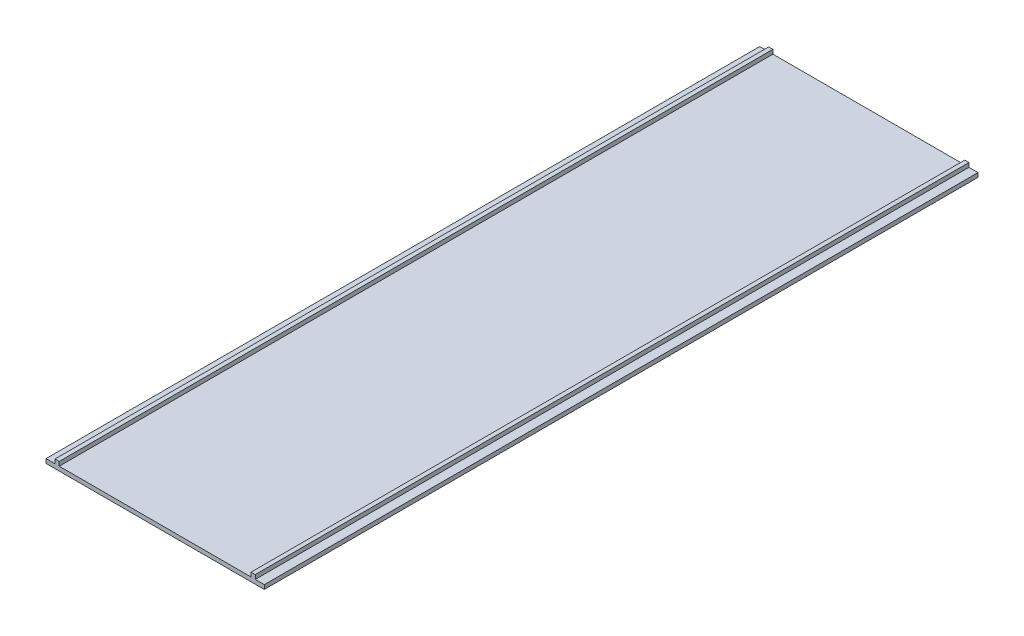
SolidWorks part; units mm, degrees
ref_plane "Спереди" through (0, 0, 0) normal (0, 0, 1) x (1, 0, 0)
ref_plane "Сверху" through (0, 0, 0) normal (0, 1, 0) x (1, 0, 0)
ref_plane "Справа" through (0, 0, 0) normal (1, 0, 0) x (0, 0, -1)
sketch "Эскиз1" plane through (0, 0, 0) normal (0, 1, 0) x (1, 0, 0)
  line L1 (-52, -170) -> (52, -170)
  line L2 (-52, -170) -> (-52, 170)
  line L3 (-52, 170) -> (52, 170)
  line L4 (52, -170) -> (52, 170)
  line L5 (-52, -170) -> (52, 170) construction
  line L6 (-52, 170) -> (52, -170) construction
  point P0 (0, 0)
  dimension "D1" = 104
  dimension "D2" = 340
extrude "Бобышка-Вытянуть1" add sketch "Эскиз1" along normal blind 2
sketch "Эскиз2" plane through (0, 0, 170) normal (0, 0, 1) x (1, 0, 0)
  line L5 (-47.7, 2) -> (-47.7, 4)
  line L6 (-52, 2) -> (52, 2) construction
  line L7 (-47.7, 4) -> (-45.7, 4)
  line L8 (-45.7, 4) -> (-45.7, 2)
  line L9 (-45.7, 2) -> (-47.7, 2)
  line L10 (0, 0) -> (0, -13.138) construction
  dimension "D1" = 91.4
  dimension "D2" = 2
  dimension "D3" = 2
extrude "Бобышка-Вытянуть2" add sketch "Эскиз2" against normal up to surface (340 mm away) up to face at (0, 1, -170)
mirror "Зеркальное отражение1" about plane through (0, 0, 0) normal (1, 0, 0) of "Бобышка-Вытянуть2"
